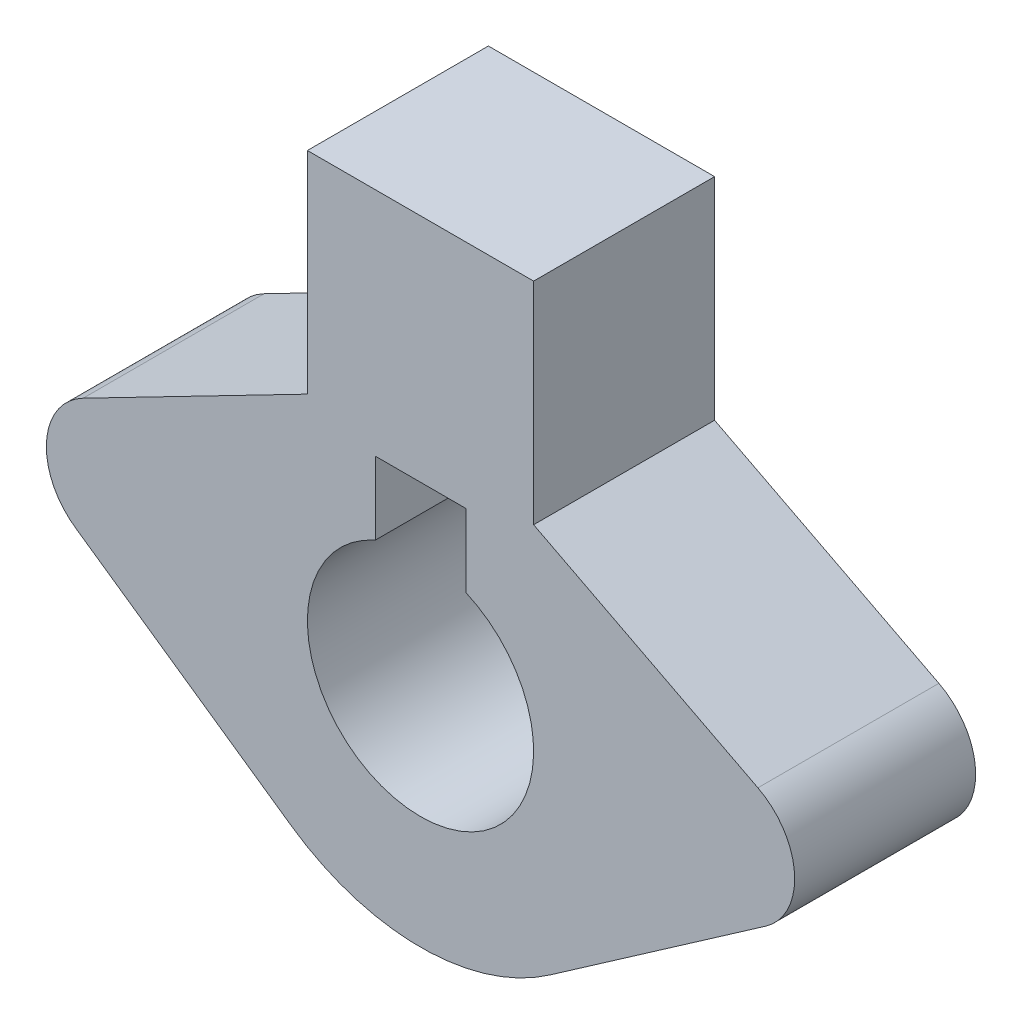
SolidWorks part; units mm, degrees
ref_plane "Front Plane" through (0, 0, 0) normal (0, 0, 1) x (1, 0, 0)
ref_plane "Top Plane" through (0, 0, 0) normal (0, 1, 0) x (1, 0, 0)
ref_plane "Right Plane" through (0, 0, 0) normal (1, 0, 0) x (0, 0, -1)
sketch "Sketch1" plane through (0, 0, 0) normal (0, 0, 1) x (1, 0, 0)
  line L0 (-5, 8.6603) -> (-5, 18)
  line L1 (-5, 18) -> (5, 18)
  line L2 (0, -55) -> (0, 55) construction
  line L3 (5, 8.6603) -> (5, 18)
  circle A0 centre (0, 0) radius 5
  arc A1 (-5, 8.6603) -> (5, 8.6603) centre (0, 0) ccw
  point P10 (0, 18)
  dimension "D1" = 10
  dimension "D2" = 20
  dimension "D3" = 18
  dimension "D4" = 5
extrude "Boss-Extrude1" add sketch "Sketch1" along normal blind 8
sketch "Sketch2" plane through (0, 0, 0) normal (0, 0, -1) x (-1, 0, 0)
  line L0 (-5.7115, -8.2084) -> (-19.3422, 1.276)
  line L1 (-19.3422, 1.276) -> (-4.5837, 8.8876)
  line L4 (0, 0) -> (0, 5.778) construction
  line L5 (5.7115, -8.2084) -> (19.3422, 1.276)
  line L6 (19.3422, 1.276) -> (4.5837, 8.8876)
  arc A1 (-5, 8.6603) -> (5, 8.6603) centre (0, 0) ccw construction
  arc A2 (-4.5837, 8.8876) -> (-5.7115, -8.2084) centre (0, 0) ccw
  arc A4 (4.5837, 8.8876) -> (5.7115, -8.2084) centre (0, 0) cw
extrude "Boss-Extrude2" add sketch "Sketch2" against normal up to surface (8 mm away) up to face at (0, 8.6651, 8)
fillet "Fillet1" radius 3 2 edges at (-19.3422, 1.276, 4) (19.3422, 1.276, 4)
sketch "Sketch3" plane through (0, 0, 0) normal (0, 0, -1) x (-1, 0, 0)
  line L1 (-2, 3.5) -> (2, 3.5)
  line L2 (-2, 3.5) -> (-2, 7.8)
  line L3 (-2, 7.8) -> (2, 7.8)
  line L4 (2, 3.5) -> (2, 7.8)
  dimension "D1" = 4
  dimension "D2" = 4.3
  dimension "D3" = 2
  dimension "D4" = 3.5
extrude "Cut-Extrude1" cut sketch "Sketch3" against normal through all
